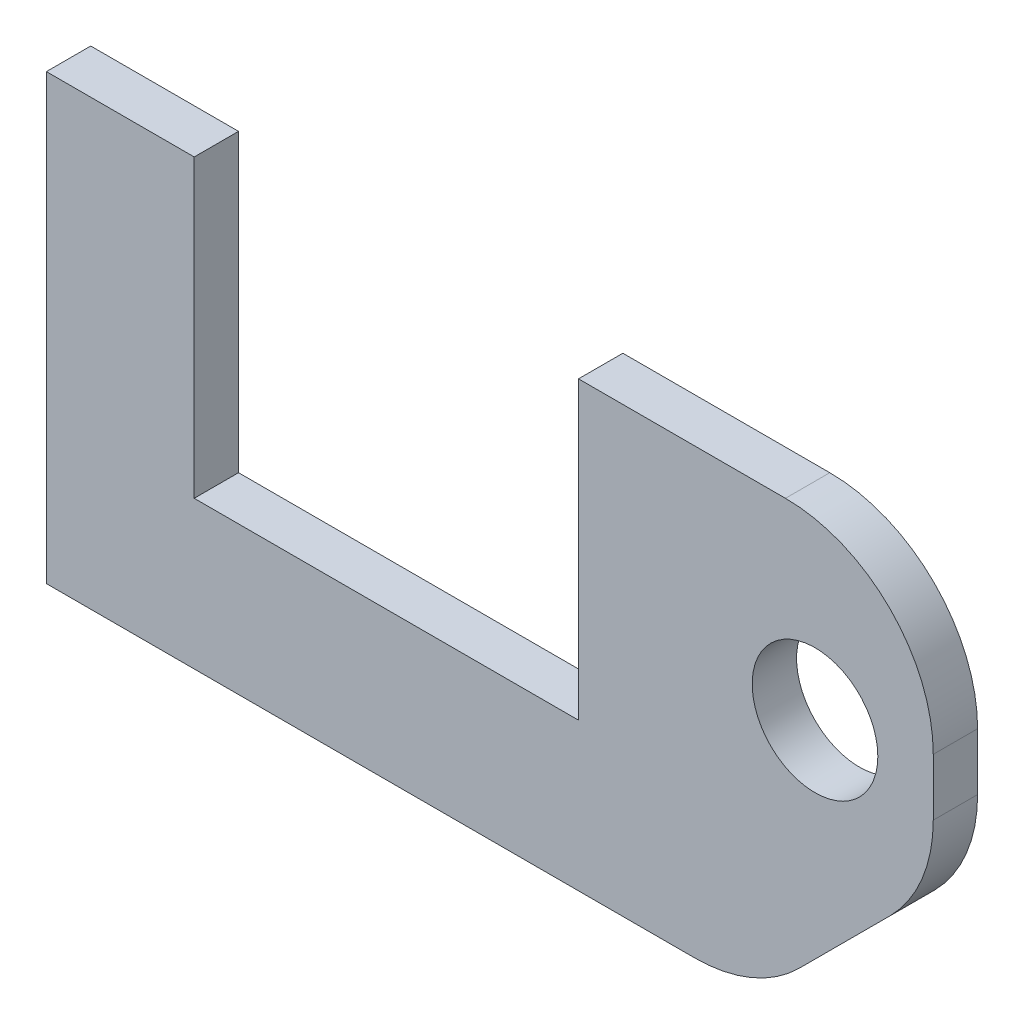
SolidWorks part; units mm, degrees
ref_plane "Front Plane" through (0, 0, 0) normal (0, 0, 1) x (1, 0, 0)
ref_plane "Top Plane" through (0, 0, 0) normal (0, 1, 0) x (1, 0, 0)
ref_plane "Right Plane" through (0, 0, 0) normal (1, 0, 0) x (0, 0, -1)
sketch "Sketch1" plane through (0, 0, 0) normal (0, 0, 1) x (1, 0, 0)
  line L0 (0, 30) -> (0, 0)
  line L1 (0, 0) -> (60, 0)
  line L2 (60, 0) -> (60, 30)
  line L3 (60, 30) -> (36, 30)
  line L4 (36, 30) -> (36, 10)
  line L5 (36, 10) -> (10, 10)
  line L6 (10, 10) -> (10, 30)
  line L7 (10, 30) -> (0, 30)
  circle A0 centre (52, 18) radius 4.25
  dimension "D6" = 8.5
  dimension "D7" = 8
  dimension "D8" = 12
  dimension "D1" = 10
  dimension "D2" = 30
  dimension "D3" = 20
  dimension "D4" = 26
  dimension "D5" = 60
extrude "Boss-Extrude1" add sketch "Sketch1" along normal blind 3
chamfer "Chamfer1" distance 12 angle 45 1 edges at (60, 0, 1.5)
fillet "Fillet1" radius 10 1 edges at (60, 30, 1.5)
fillet "Fillet2" radius 10 2 edges at (60, 12, 1.5) (48, 0, 1.5)
